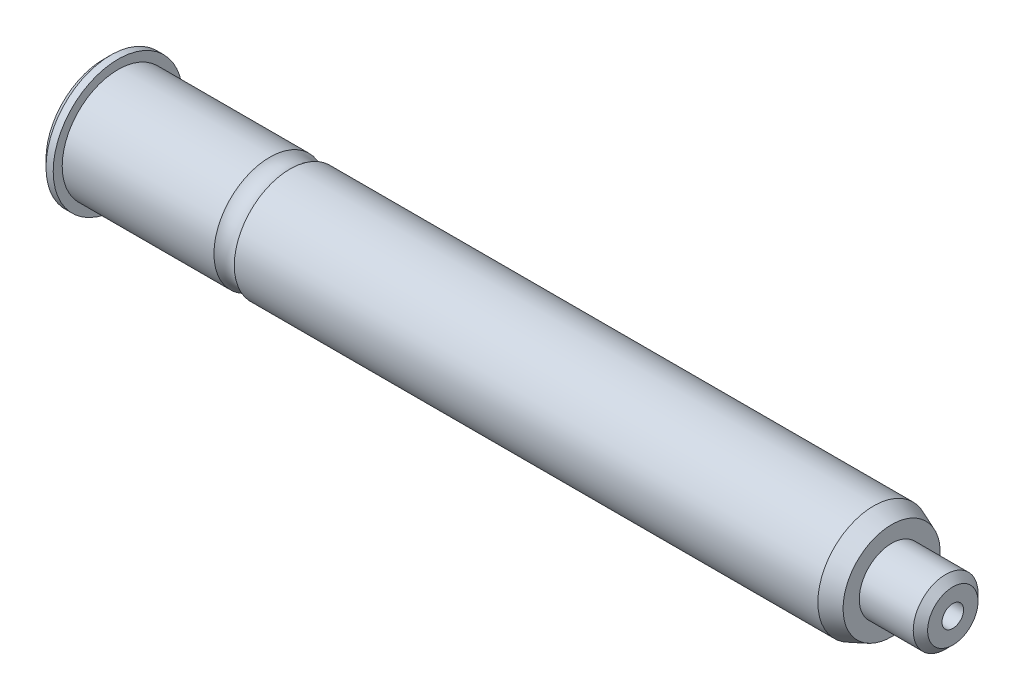
SolidWorks part; units mm, degrees
ref_plane "Plan1" through (0, 0, 0) normal (0, 0, 1) x (1, 0, 0)
ref_plane "Plan2" through (0, 0, 0) normal (0, 1, 0) x (1, 0, 0)
ref_plane "Plan3" through (0, 0, 0) normal (1, 0, 0) x (0, 0, -1)
sketch "Esquisse1" plane through (0, 0, 0) normal (0, 0, 1) x (1, 0, 0)
  line L0 (0, 0) -> (0, -9)
  line L1 (0, -9) -> (2, -9)
  line L2 (2, -9) -> (2, -7.75)
  line L3 (2, -7.75) -> (23.0858, -7.75)
  line L4 (109.5, -6.75) -> (109.5, -4.5)
  line L5 (109.5, -4.5) -> (118, -4.5)
  line L6 (118, -4.5) -> (118, 0)
  line L7 (0, 0) -> (118, 0)
  line L8 (-10, 0) -> (120, 0) construction
  line L9 (109.5, -6.75) -> (107, -7.75)
  line L10 (25.9142, -7.75) -> (107, -7.75)
  arc A0 (25.9142, -7.75) -> (23.0858, -7.75) centre (24.5, -9.5) ccw
  dimension "D9" = 4.5
  dimension "D10" = 9.5
  dimension "D11" = 24.5
  dimension "D1" = 4.5
  dimension "D2" = 7.75
  dimension "D3" = 9
  dimension "D4" = 2
  dimension "D5" = 8.5
  dimension "D6" = 116
  dimension "D7" = 2.5
  dimension "D8" = 1
revolve "Base-Révolution" add sketch "Esquisse1" angle 360 about L8
chamfer "Chanfrein1" distance 1 angle 45
hole_wizard "Perçage1" positions "Esquisse3" profile "Esquisse2" legacy
sketch "Esquisse3" plane through (118, 0, 0) normal (1, 0, 0) x (0, 0, -1)
  point P0 (0, 0)
sketch "Esquisse2" plane through (118, 0, 0) normal (0, 1, 0) x (0, 0, -1)
  line L0 (0, 0) -> (0, 25.9013)
  line L1 (0, 25.9013) -> (1.5, 25)
  line L2 (1.5, 25) -> (1.5, 0)
  line L4 (1.5, 0) -> (0, 0)
  line L6 (0, 25.9013) -> (-1.5, 25) construction
  line L7 (0, -4.2442) -> (0, 117.3081) construction
  dimension "Diamètre" = 3
  dimension "Profondeur" = 25
  dimension "Angle" = 118
cosmetic thread "Représentation de filetage1" parameters "D1"=20, "D2"=4
